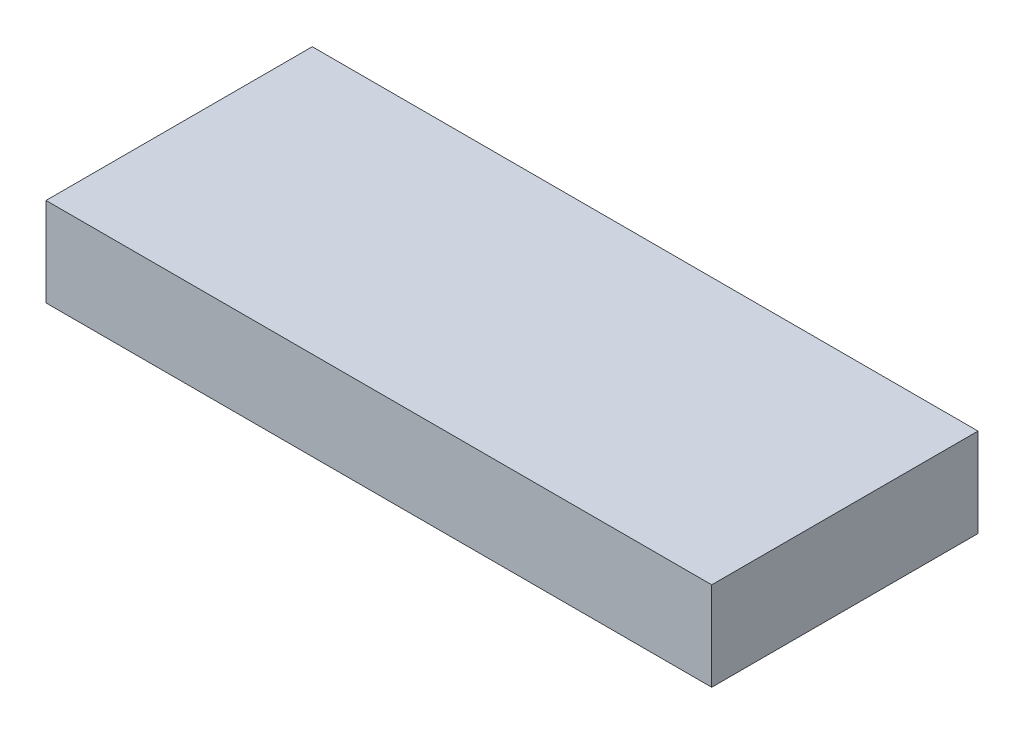
SolidWorks part; units mm, degrees
ref_plane "Front Plane" through (0, 0, 0) normal (0, 0, 1) x (1, 0, 0)
ref_plane "Top Plane" through (0, 0, 0) normal (0, 1, 0) x (1, 0, 0)
ref_plane "Right Plane" through (0, 0, 0) normal (1, 0, 0) x (0, 0, -1)
sketch "Sketch1" plane through (0, 0, 0) normal (0, 1, 0) x (1, 0, 0)
  line L1 (-21.7793, 8.5273) -> (38.2207, 8.5273)
  line L2 (-21.7793, 8.5273) -> (-21.7793, -15.4727)
  line L3 (-21.7793, -15.4727) -> (38.2207, -15.4727)
  line L4 (38.2207, 8.5273) -> (38.2207, -15.4727)
  dimension "D1" = 60
  dimension "D2" = 24
extrude "Extrude1" add sketch "Sketch1" along normal blind 8
